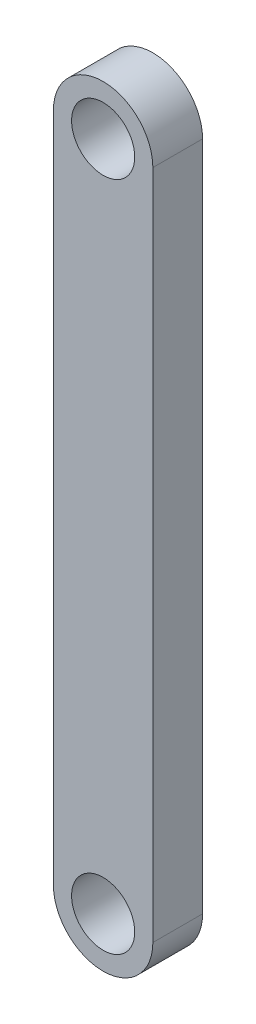
SolidWorks part; units mm, degrees
ref_plane "Front Plane" through (0, 0, 0) normal (0, 0, 1) x (1, 0, 0)
ref_plane "Top Plane" through (0, 0, 0) normal (0, 1, 0) x (1, 0, 0)
ref_plane "Right Plane" through (0, 0, 0) normal (1, 0, 0) x (0, 0, -1)
sketch "Sketch1" plane through (0, 0, 0) normal (0, 0, 1) x (1, 0, 0)
  line L0 (0, 0) -> (0, 135) construction
  line L1 (-10, 0) -> (-10, 135)
  line L2 (10, 0) -> (10, 135)
  arc A0 (-10, 0) -> (10, 0) centre (0, 0) ccw
  arc A1 (10, 135) -> (-10, 135) centre (0, 135) ccw
  point P3 (0, 67.5)
  dimension "D1" = 135
  dimension "D2" = 20
extrude "Boss-Extrude1" add sketch "Sketch1" along normal blind 10
sketch "Sketch2" plane through (0, 0, 10) normal (0, 0, 1) x (1, 0, 0)
  circle A0 centre (0, 135) radius 6.35
  circle A1 centre (0, 0) radius 6.35
  dimension "D1" = 12.7
  dimension "D2" = 12.7
extrude "Cut-Extrude1" cut sketch "Sketch2" against normal through all
